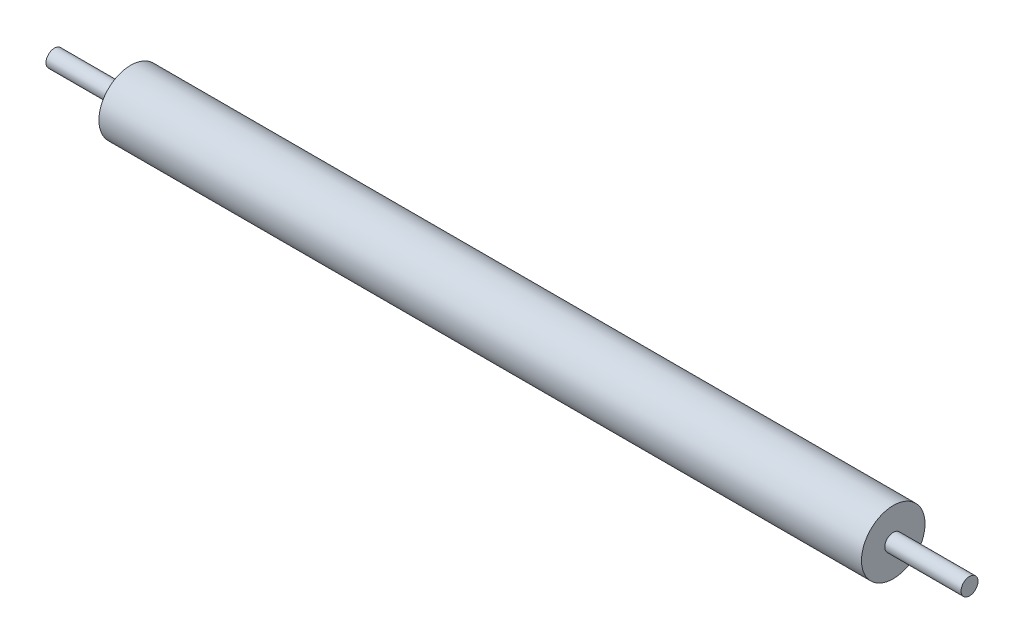
SolidWorks part; units mm, degrees
ref_plane "Front Plane" through (0, 0, 0) normal (0, 0, 1) x (1, 0, 0)
ref_plane "Top Plane" through (0, 0, 0) normal (0, 1, 0) x (1, 0, 0)
ref_plane "Right Plane" through (0, 0, 0) normal (1, 0, 0) x (0, 0, -1)
sketch "Sketch2" plane through (0, 0, 0) normal (1, 0, 0) x (0, 0, -1)
  circle A0 centre (0, 0) radius 15
extrude "Boss-Extrude1" add sketch "Sketch2" along normal blind 180
sketch "Sketch3" plane through (180, 0, 0) normal (1, 0, 0) x (0, 0, -1)
  circle A0 centre (0, 0) radius 4
extrude "Boss-Extrude2" add sketch "Sketch3" along normal blind 36
mirror "Mirror1" about plane through (0, 0, 0) normal (1, 0, 0) of "Boss-Extrude1", "Boss-Extrude2"
